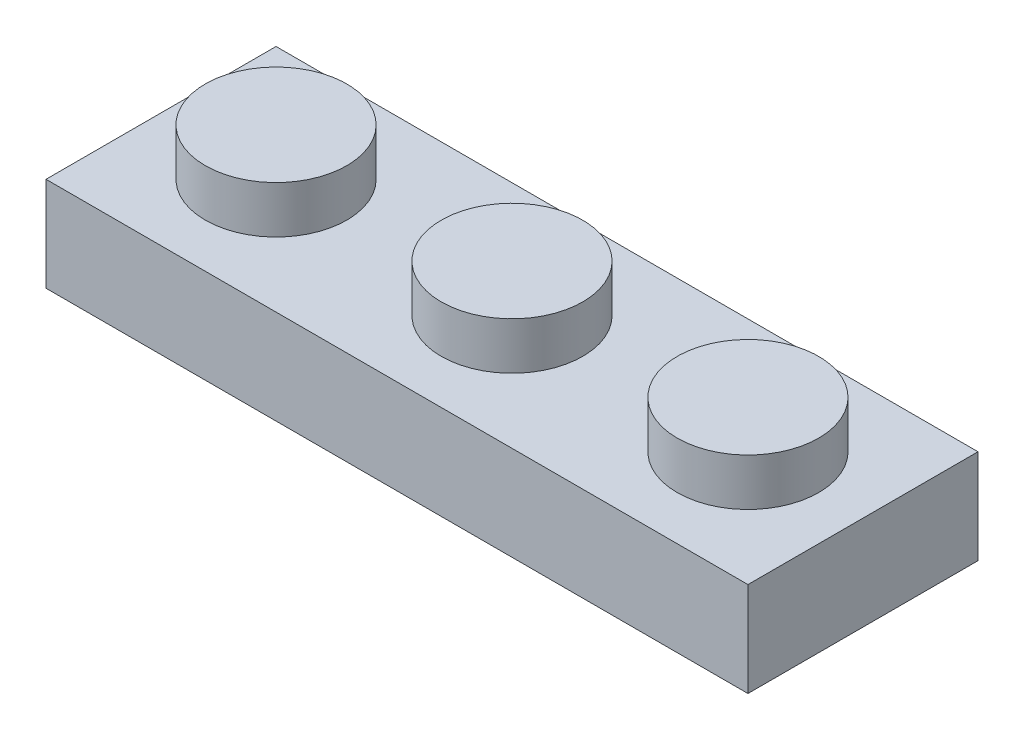
SolidWorks part; units mm, degrees
material "ABS"
ref_plane "Front Plane" through (0, 0, 0) normal (0, 0, 1) x (1, 0, 0)
ref_plane "Top Plane" through (0, 0, 0) normal (0, 1, 0) x (1, 0, 0)
ref_plane "Right Plane" through (0, 0, 0) normal (1, 0, 0) x (0, 0, -1)
sketch "Sketch1" plane through (0, 0, 0) normal (0, 0, 1) x (1, 0, 0)
  line L1 (0, 0) -> (23.8, 0)
  line L2 (0, 0) -> (0, 3.2)
  line L3 (0, 3.2) -> (23.8, 3.2)
  line L4 (23.8, 0) -> (23.8, 3.2)
  line L5 (0, 0) -> (23.8, 3.2) construction
  line L6 (0, 3.2) -> (23.8, 0) construction
  point P4 (11.9, 1.6)
  dimension "D1" = 23.8
  dimension "D2" = 3.2
extrude "Boss-Extrude1" add sketch "Sketch1" against normal blind 7.8
sketch "Sketch2" plane through (0, 3.2, 0) normal (0, 1, 0) x (1, 0, 0)
  line L0 (23.8, 0) -> (0, 0) construction
  circle A0 centre (3.9, 3.9) radius 2.4
  dimension "D1" = 4.8
  dimension "D2" = 3.9
  dimension "D3" = 3.9
extrude "Boss-Extrude2" add sketch "Sketch2" along normal blind 1.6
pattern_linear "LPattern1" count 2 spacing 8 along (0, 0, 1) count 4 spacing 8 along (1, 0, 0) of "Boss-Extrude2"
shell "Shell1" thickness 1.2
sketch "Sketch3" plane through (0, 2, 0) normal (0, -1, 0) x (1, 0, 0)
  line L0 (0, 0) -> (23.8, 0) construction
  line L1 (0, -7.8) -> (0, 0) construction
  circle A0 centre (7.9, -3.9) radius 1.5
  circle A1 centre (7.9, -3.9) radius 0.6
  dimension "D1" = 3
  dimension "D2" = 1.2
  dimension "D3" = 3.9
  dimension "D4" = 7.9
extrude "Boss-Extrude3" add sketch "Sketch3" along normal offset from surface (1.8 mm away) 0.2 up to face at (11.9, 0, -3.9)
pattern_linear "LPattern2" count 2 spacing 8 along (1, 0, 0) of "Boss-Extrude3"
